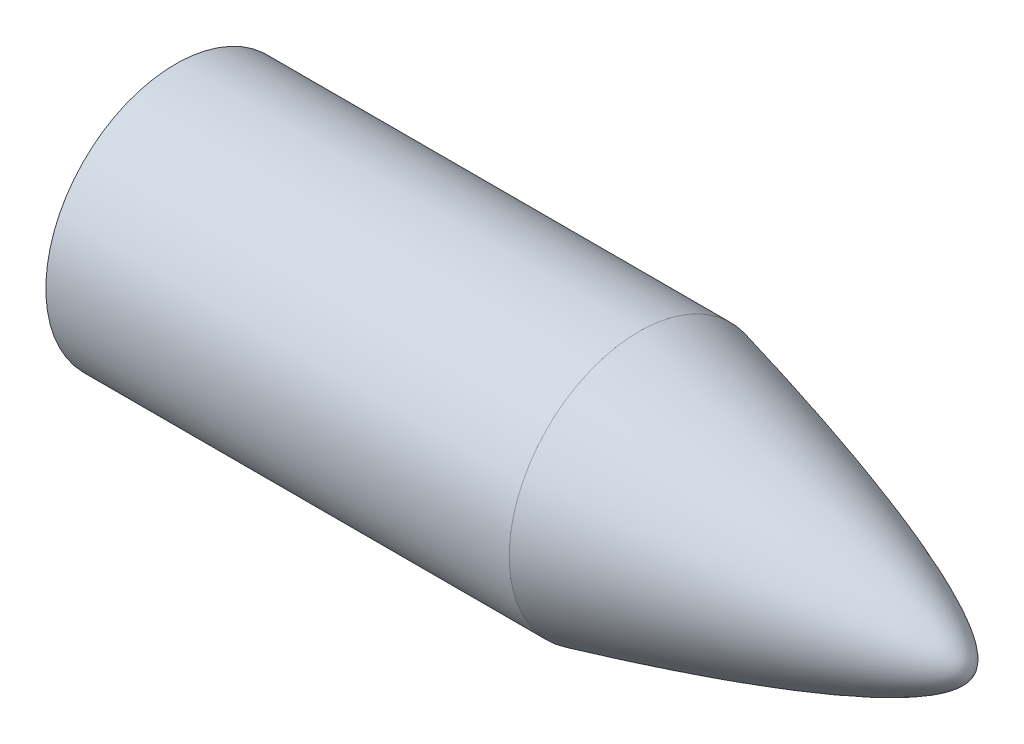
SolidWorks part; units mm, degrees
ref_plane "Front Plane" through (0, 0, 0) normal (0, 0, 1) x (1, 0, 0)
ref_plane "Top Plane" through (0, 0, 0) normal (0, 1, 0) x (1, 0, 0)
ref_plane "Right Plane" through (0, 0, 0) normal (1, 0, 0) x (0, 0, -1)
sketch "Sketch1" plane through (0, 0, 0) normal (0, 1, 0) x (1, 0, 0)
  line L0 (89.9559, 0) -> (214.9559, 0)
  line L1 (-85.0441, 49) -> (89.9559, 49)
  line L2 (-85.0441, 49) -> (-85.0441, 0)
  line L3 (-85.0441, 0) -> (89.9559, 0)
  line L4 (89.9559, 49) -> (89.9559, 0)
  line L5 (-85.0441, 0) -> (214.9559, 0)
  line L6 (132.8015, 0) -> (-191.2164, 0)
  line L7 (-191.2164, 0) -> (132.8015, 0)
  ellipse E0 centre (-85.0441, 49) end of major axis (214.9559, 0) minor radius 34.2803 (89.9559, 49) -> (214.9559, 0) cw
  dimension "D1" = 49
  dimension "D2" = 175
  dimension "D3" = 125
revolve "Revolve4" add sketch "Sketch1" angle 360 about L6
